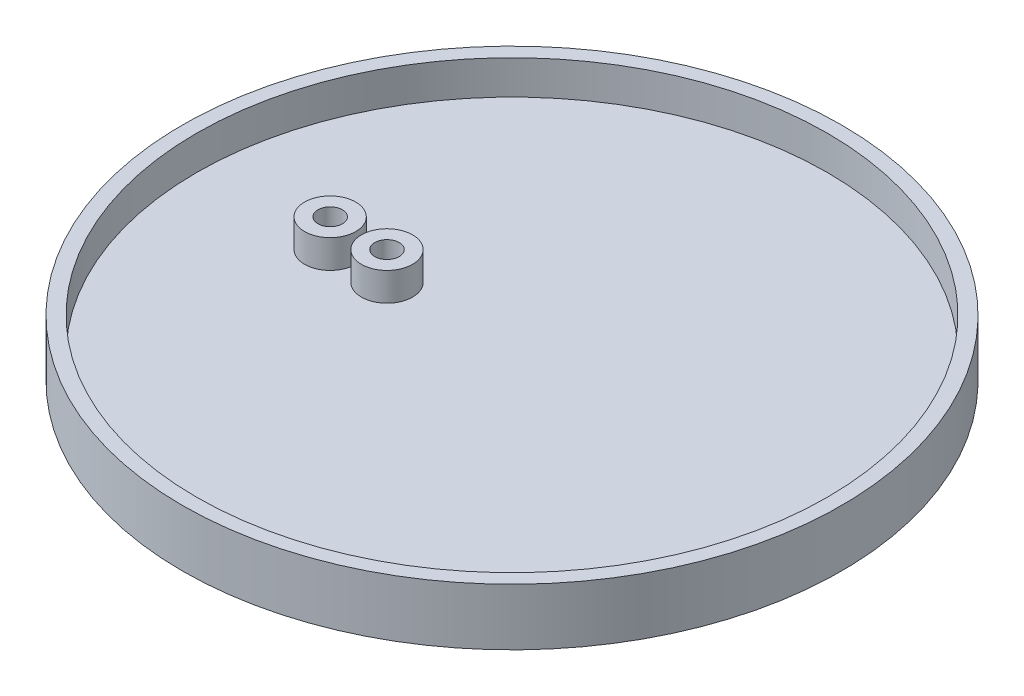
SolidWorks part; units mm, degrees
ref_plane "前视基准面" through (0, 0, 0) normal (0, 0, 1) x (1, 0, 0)
ref_plane "上视基准面" through (0, 0, 0) normal (0, 1, 0) x (1, 0, 0)
ref_plane "右视基准面" through (0, 0, 0) normal (1, 0, 0) x (0, 0, -1)
other "Configuration Table"
sketch "草图1" plane through (0, 0, 0) normal (0, 1, 0) x (1, 0, 0)
  circle A0 centre (-22, 0) radius 4.5
extrude "Moving_post_A" add sketch "草图1" along normal blind 9
sketch "草图2" plane through (0, 0, 0) normal (0, 1, 0) x (1, 0, 0)
  circle A0 centre (0, 0) radius 58
extrude "Cup_plate_D116_T4" add sketch "草图2" along normal blind 4
sketch "草图3" plane through (0, 0, 0) normal (0, 1, 0) x (1, 0, 0)
  circle A0 centre (-32, 0) radius 4.5
extrude "Moving_post_B" add sketch "草图3" along normal blind 9
sketch "草图4" plane through (0, 0, 0) normal (0, 1, 0) x (1, 0, 0)
  circle A0 centre (0, 0) radius 58
  circle A1 centre (0, 0) radius 55.5
extrude "Drip_skirt_OD116_ID111_H10" add sketch "草图4" along normal blind 10
sketch "草图5" plane through (0, 0, 0) normal (0, 1, 0) x (1, 0, 0)
  circle A0 centre (-22, 0) radius 2.15
  circle A1 centre (-32, 0) radius 2.15
extrude "M4_moving_mount_clearance" cut sketch "草图5" along normal blind 9
